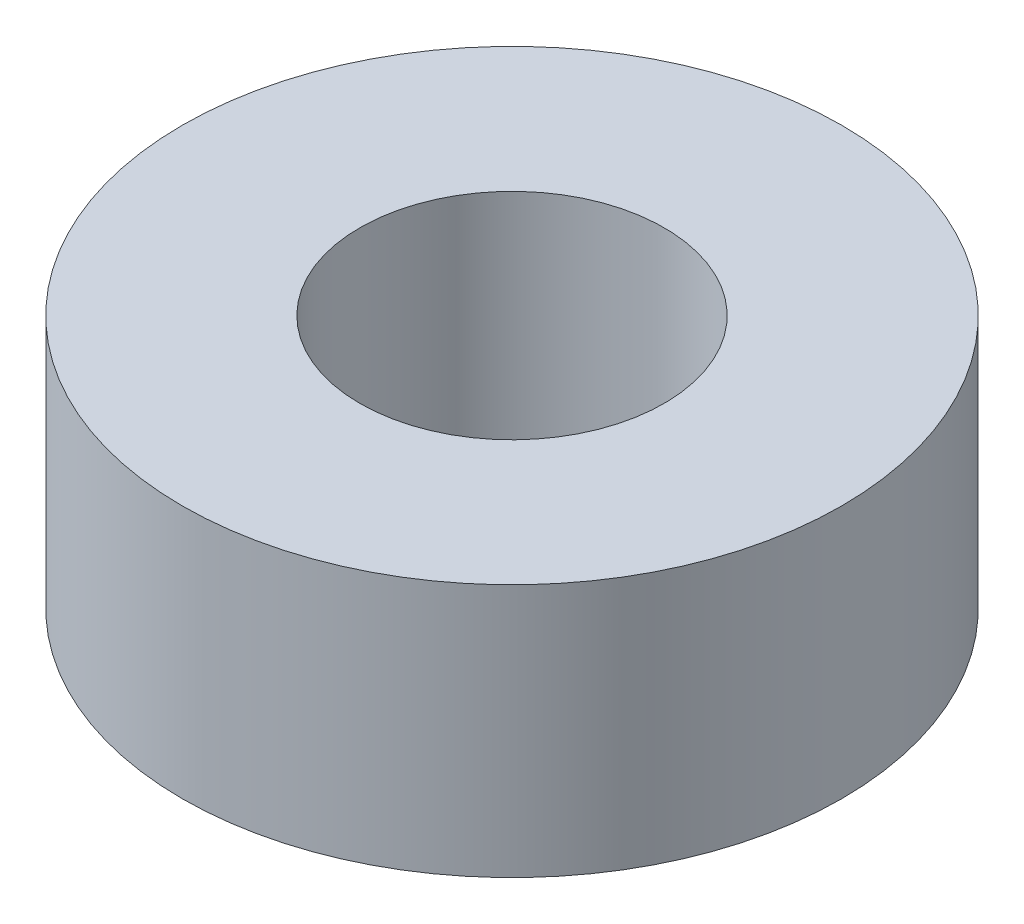
SolidWorks part; units mm, degrees
ref_plane "Front Plane" through (0, 0, 0) normal (0, 0, 1) x (1, 0, 0)
ref_plane "Top Plane" through (0, 0, 0) normal (0, 1, 0) x (1, 0, 0)
ref_plane "Right Plane" through (0, 0, 0) normal (1, 0, 0) x (0, 0, -1)
sketch "Sketch1" plane through (0, 0, 0) normal (0, 1, 0) x (1, 0, 0)
  circle A0 centre (0, 0) radius 6.5
  circle A1 centre (0, 0) radius 3
  dimension "D1" = 13
  dimension "D2" = 6
extrude "Boss-Extrude1" add sketch "Sketch1" along normal blind 5
